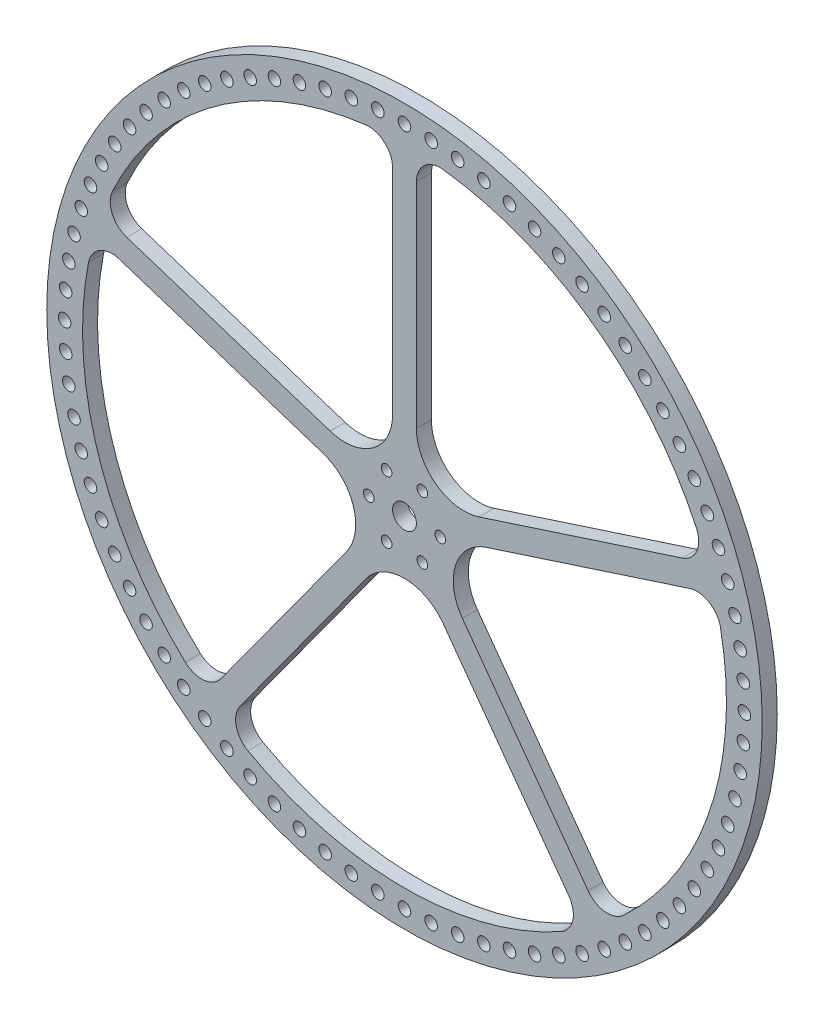
SolidWorks part; units mm, degrees
ref_plane "Front Plane" through (0, 0, 0) normal (0, 0, 1) x (1, 0, 0)
ref_plane "Top Plane" through (0, 0, 0) normal (0, 1, 0) x (1, 0, 0)
ref_plane "Right Plane" through (0, 0, 0) normal (1, 0, 0) x (0, 0, -1)
sketch "Model" plane through (0, 0, 0) normal (0, 0, 1) x (1, 0, 0)
  line L0 (21.7618, 3.7324) -> (75.9257, 21.3314)
  line L1 (48.8869, -61.8855) -> (15.4118, -15.8109)
  line L2 (10.2745, -19.5433) -> (43.7497, -65.6179)
  line L3 (-43.7497, -65.6179) -> (-10.2745, -19.5433)
  line L4 (-15.4118, -15.8109) -> (-48.8869, -61.8855)
  line L5 (-75.9257, 21.3314) -> (-21.7618, 3.7324)
  line L6 (-19.7995, 9.7716) -> (-73.9635, 27.3706)
  line L7 (-3.175, 78.8014) -> (-3.175, 21.8501)
  line L8 (73.9635, 27.3706) -> (19.7995, 9.7716)
  line L9 (3.175, 21.8501) -> (3.175, 78.8014)
  circle A0 centre (0, 0) radius 3.175
  circle A1 centre (7.0996, 90.2086) radius 1.6724
  circle A2 centre (14.1554, 89.3734) radius 1.6724
  circle A3 centre (21.1239, 87.9873) radius 1.6724
  circle A4 centre (27.9622, 86.0587) radius 1.6724
  circle A5 centre (34.6281, 83.5995) radius 1.6724
  circle A6 centre (41.0805, 80.625) radius 1.6724
  circle A7 centre (47.2796, 77.1533) radius 1.6724
  circle A8 centre (53.1872, 73.2059) radius 1.6724
  circle A9 centre (58.7669, 68.8072) radius 1.6724
  circle A10 centre (63.9843, 63.9843) radius 1.6724
  circle A11 centre (68.8072, 58.7669) radius 1.6724
  circle A12 centre (73.2059, 53.1872) radius 1.6724
  circle A13 centre (77.1533, 47.2796) radius 1.6724
  circle A14 centre (80.625, 41.0805) radius 1.6724
  circle A15 centre (83.5995, 34.6281) radius 1.6724
  circle A16 centre (86.0587, 27.9622) radius 1.6724
  circle A17 centre (87.9873, 21.1239) radius 1.6724
  circle A18 centre (89.3734, 14.1554) radius 1.6724
  circle A19 centre (90.2086, 7.0996) radius 1.6724
  circle A20 centre (90.4875, 0) radius 1.6724
  circle A21 centre (90.2086, -7.0996) radius 1.6724
  circle A22 centre (89.3734, -14.1554) radius 1.6724
  circle A23 centre (87.9873, -21.1239) radius 1.6724
  circle A24 centre (86.0587, -27.9622) radius 1.6724
  circle A25 centre (83.5995, -34.6281) radius 1.6724
  circle A26 centre (80.625, -41.0805) radius 1.6724
  circle A27 centre (77.1533, -47.2796) radius 1.6724
  circle A28 centre (73.2059, -53.1872) radius 1.6724
  circle A29 centre (68.8072, -58.7669) radius 1.6724
  circle A30 centre (63.9843, -63.9843) radius 1.6724
  circle A31 centre (58.7669, -68.8072) radius 1.6724
  circle A32 centre (53.1872, -73.2059) radius 1.6724
  circle A33 centre (47.2796, -77.1533) radius 1.6724
  circle A34 centre (41.0805, -80.625) radius 1.6724
  circle A35 centre (34.6281, -83.5995) radius 1.6724
  circle A36 centre (27.9622, -86.0587) radius 1.6724
  circle A37 centre (21.1239, -87.9873) radius 1.6724
  circle A38 centre (14.1554, -89.3734) radius 1.6724
  circle A39 centre (7.0996, -90.2086) radius 1.6724
  circle A40 centre (0, -90.4875) radius 1.6724
  circle A41 centre (-7.0996, -90.2086) radius 1.6724
  circle A42 centre (-14.1554, -89.3734) radius 1.6724
  circle A43 centre (-21.1239, -87.9873) radius 1.6724
  circle A44 centre (-27.9622, -86.0587) radius 1.6724
  circle A45 centre (-34.6281, -83.5995) radius 1.6724
  circle A46 centre (-41.0805, -80.625) radius 1.6724
  circle A47 centre (-47.2796, -77.1533) radius 1.6724
  circle A48 centre (-53.1872, -73.2059) radius 1.6724
  circle A49 centre (-58.7669, -68.8072) radius 1.6724
  circle A50 centre (-63.9843, -63.9843) radius 1.6724
  circle A51 centre (-68.8072, -58.7669) radius 1.6724
  circle A52 centre (-73.2059, -53.1872) radius 1.6724
  circle A53 centre (-77.1533, -47.2796) radius 1.6724
  circle A54 centre (-80.625, -41.0805) radius 1.6724
  circle A55 centre (-83.5995, -34.6281) radius 1.6724
  circle A56 centre (-86.0587, -27.9622) radius 1.6724
  circle A57 centre (-87.9873, -21.1239) radius 1.6724
  circle A58 centre (-89.3734, -14.1554) radius 1.6724
  circle A59 centre (-90.2086, -7.0996) radius 1.6724
  circle A60 centre (-90.4875, 0) radius 1.6724
  circle A61 centre (-90.2086, 7.0996) radius 1.6724
  circle A62 centre (-89.3734, 14.1554) radius 1.6724
  circle A63 centre (-87.9873, 21.1239) radius 1.6724
  circle A64 centre (-86.0587, 27.9622) radius 1.6724
  circle A65 centre (-83.5995, 34.6281) radius 1.6724
  circle A66 centre (-80.625, 41.0805) radius 1.6724
  circle A67 centre (-77.1533, 47.2796) radius 1.6724
  circle A68 centre (-73.2059, 53.1872) radius 1.6724
  circle A69 centre (-68.8072, 58.7669) radius 1.6724
  circle A70 centre (-63.9843, 63.9843) radius 1.6724
  circle A71 centre (-58.7669, 68.8072) radius 1.6724
  circle A72 centre (-53.1872, 73.2059) radius 1.6724
  circle A73 centre (-47.2796, 77.1533) radius 1.6724
  circle A74 centre (-41.0805, 80.625) radius 1.6724
  circle A75 centre (-34.6281, 83.5995) radius 1.6724
  circle A76 centre (-27.9622, 86.0587) radius 1.6724
  circle A77 centre (-21.1239, 87.9873) radius 1.6724
  circle A78 centre (-14.1554, 89.3734) radius 1.6724
  circle A79 centre (-7.0996, 90.2086) radius 1.6724
  circle A80 centre (0, 90.4875) radius 1.6724
  circle A81 centre (4.7625, -8.2489) radius 1.4224
  circle A82 centre (-4.7625, -8.2489) radius 1.4224
  circle A83 centre (-9.525, 0) radius 1.4224
  circle A84 centre (-4.7625, 8.2489) radius 1.4224
  circle A85 centre (4.7625, 8.2489) radius 1.4224
  circle A86 centre (9.525, 0) radius 1.4224
  circle A87 centre (0, 0) radius 95.25
  arc A88 (84.119, 16.5155) -> (75.9257, 21.3314) centre (77.888, 15.2922) ccw
  arc A89 (58.3461, -62.8053) -> (84.119, 16.5155) centre (0, 0) ccw
  arc A90 (48.8869, -61.8855) -> (58.3461, -62.8053) centre (54.0242, -58.153) ccw
  arc A91 (21.7618, 3.7324) -> (15.4118, -15.8109) centre (25.6863, -8.346) ccw
  arc A92 (41.7014, -74.8984) -> (43.7497, -65.6179) centre (38.6124, -69.3503) ccw
  arc A93 (-41.7014, -74.8984) -> (41.7014, -74.8984) centre (0, 0) ccw
  arc A94 (-43.7497, -65.6179) -> (-41.7014, -74.8984) centre (-38.6124, -69.3503) ccw
  arc A95 (10.2745, -19.5433) -> (-10.2745, -19.5433) centre (0, -27.0082) ccw
  arc A96 (-58.3461, -62.8053) -> (-48.8869, -61.8855) centre (-54.0242, -58.153) ccw
  arc A97 (-84.119, 16.5155) -> (-58.3461, -62.8053) centre (0, 0) ccw
  arc A98 (-75.9257, 21.3314) -> (-84.119, 16.5155) centre (-77.888, 15.2922) ccw
  arc A99 (-15.4118, -15.8109) -> (-21.7618, 3.7324) centre (-25.6863, -8.346) ccw
  arc A100 (-77.7613, 36.0826) -> (-73.9635, 27.3706) centre (-72.0012, 33.4098) ccw
  arc A101 (-10.287, 85.1055) -> (-77.7613, 36.0826) centre (0, 0) ccw
  arc A102 (-3.175, 78.8014) -> (-10.287, 85.1055) centre (-9.525, 78.8014) ccw
  arc A103 (-19.7995, 9.7716) -> (-3.175, 21.8501) centre (-15.875, 21.8501) ccw
  arc A104 (77.7613, 36.0826) -> (10.287, 85.1055) centre (0, 0) ccw
  arc A105 (73.9635, 27.3706) -> (77.7613, 36.0826) centre (72.0012, 33.4098) ccw
  arc A106 (3.175, 21.8501) -> (19.7995, 9.7716) centre (15.875, 21.8501) ccw
  arc A107 (10.287, 85.1055) -> (3.175, 78.8014) centre (9.525, 78.8014) ccw
extrude "Boss-Extrude1" add sketch "Model" along normal blind 4
